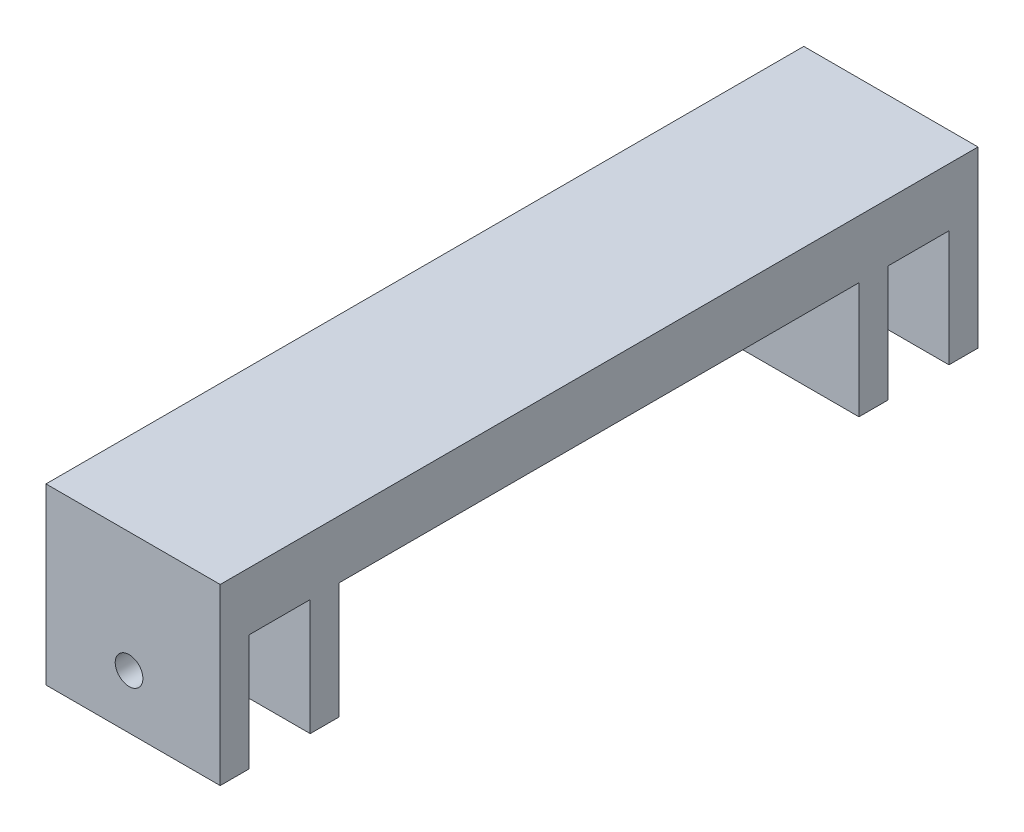
SolidWorks part; units mm, degrees
ref_plane "Plan de face" through (0, 0, 0) normal (0, 0, 1) x (1, 0, 0)
ref_plane "Plan de dessus" through (0, 0, 0) normal (0, 1, 0) x (1, 0, 0)
ref_plane "Plan de droite" through (0, 0, 0) normal (1, 0, 0) x (0, 0, -1)
sketch "Esquisse1" plane through (0, 0, 0) normal (0, 0, 1) x (1, 0, 0)
  line L1 (0, 0) -> (30, 0)
  line L2 (0, 0) -> (0, 10)
  line L3 (0, 10) -> (30, 10)
  line L4 (30, 0) -> (30, 10)
  dimension "D1" = 30
  dimension "D2" = 10
extrude "Boss.-Extru.1" add sketch "Esquisse1" along normal blind 130.5
sketch "Esquisse2" plane through (0, 0, 0) normal (0, -1, 0) x (1, 0, 0)
  line L0 (30, 130.5) -> (30, 0) construction
  line L1 (0, 0) -> (30, 0)
  line L2 (0, 0) -> (0, 5)
  line L3 (0, 5) -> (30, 5)
  line L4 (30, 0) -> (30, 5)
  line L5 (0, 130.5) -> (0, 0) construction
  line L6 (30, 15.5) -> (0, 15.5)
  line L7 (30, 15.5) -> (30, 20.5)
  line L8 (30, 20.5) -> (0, 20.5)
  line L9 (0, 15.5) -> (0, 20.5)
  line L11 (0, 130.5) -> (30, 130.5)
  line L12 (0, 130.5) -> (0, 125.5)
  line L13 (0, 125.5) -> (30, 125.5)
  line L14 (30, 130.5) -> (30, 125.5)
  line L15 (30, 115) -> (0, 115)
  line L16 (30, 115) -> (30, 110)
  line L17 (30, 110) -> (0, 110)
  line L18 (0, 115) -> (0, 110)
  dimension "D1" = 5
  dimension "D2" = 5
  dimension "D3" = 5
  dimension "D4" = 5
  dimension "D5" = 10.5
  dimension "D6" = 10.5
extrude "Boss.-Extru.2" add sketch "Esquisse2" along normal blind 20
sketch "Esquisse3" plane through (0, 0, 130.5) normal (0, 0, 1) x (1, 0, 0)
  line L0 (30, -20) -> (0, -20) construction
  line L1 (30, -20) -> (30, 10) construction
  circle A0 centre (14.3021, -10.6869) radius 1
  dimension "D1" = 2
  dimension "D2" = 9.3131
  dimension "D3" = 15.6979
hole_wizard "Perçage pour écrous auto-bloquants 300® #6 (SP)1" positions "Esquisse4" profile "Esquisse5" hole size "#6-32" standard "PEM® Inch" end condition through all
sketch "Esquisse4" plane through (0, 0, 130.5) normal (0, 0, 1) x (1, 0, 0)
  point P0 (14.3021, -10.6869)
sketch "Esquisse5" plane through (14.3021, -10.6869, 130.5) normal (1, 0, 0) x (0, -1, 0)
  line L0 (0, 0) -> (0, 130.5)
  line L1 (0, 130.5) -> (2.3812, 130.5)
  line L2 (2.3812, 130.5) -> (2.3812, 0)
  line L5 (2.3812, 0) -> (0, 0)
  line L11 (0, -6.35) -> (0, 107.95) construction
  dimension "Diamètre du perçage jusqu'au prochain" = 4.7625
  dimension "Profondeur du perçage jusqu'au prochain" = 130.5
